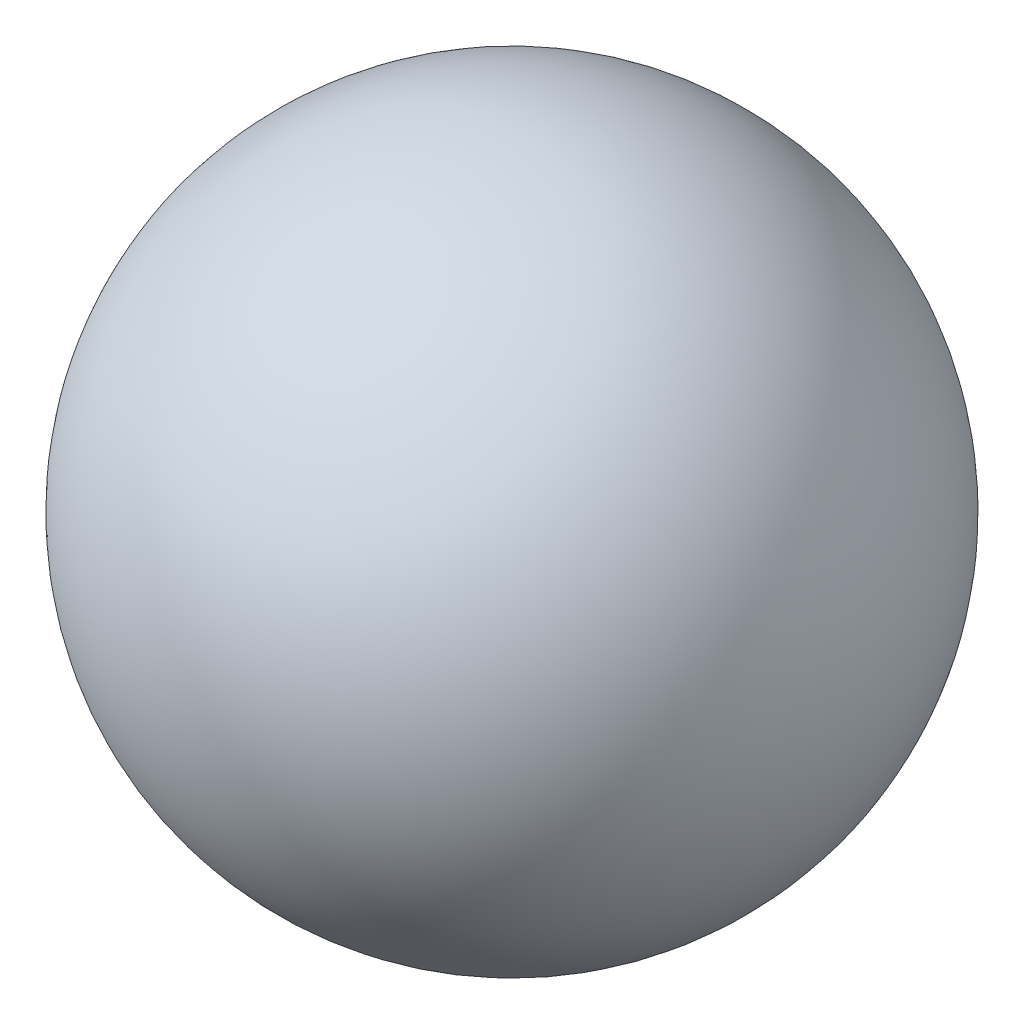
SolidWorks part; units mm, degrees
ref_plane "Ön Düzlem" through (0, 0, 0) normal (0, 0, 1) x (1, 0, 0)
ref_plane "Üst Düzlem" through (0, 0, 0) normal (0, 1, 0) x (1, 0, 0)
ref_plane "Sağ Düzlem" through (0, 0, 0) normal (1, 0, 0) x (0, 0, -1)
sketch "Çizim1" plane through (0, 0, 0) normal (0, 0, 1) x (1, 0, 0)
  line L0 (-12, 0) -> (12, 0)
  arc A0 (12, 0) -> (-12, 0) centre (0, 0) cw
  dimension "D1" = 24
revolve "Döndür1" add sketch "Çizim1" angle 360 about L0
